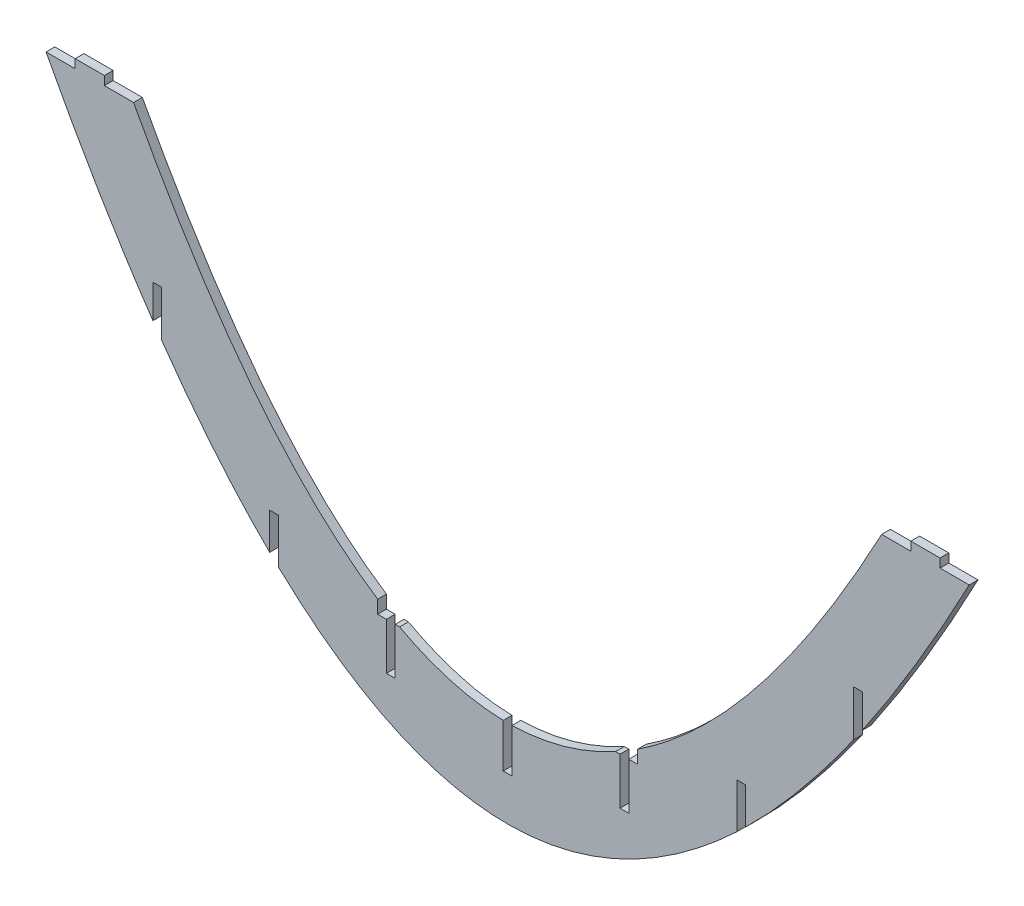
SolidWorks part; units mm, degrees
ref_plane "前视基准面" through (0, 0, 0) normal (0, 0, 1) x (1, 0, 0)
ref_plane "上视基准面" through (0, 0, 0) normal (0, 1, 0) x (1, 0, 0)
ref_plane "右视基准面" through (0, 0, 0) normal (1, 0, 0) x (0, 0, -1)
sketch "草图1" plane through (0, 0, 0) normal (0, 0, 1) x (1, 0, 0)
  line L0 (-158.115, 150.0021) -> (-128.1161, 150.0021)
  line L1 (128.1161, 150.0021) -> (158.115, 150.0021)
  spline S0 degree 2 poles (-178.3817, 190.9203) (0, -190.9203) (178.3817, 190.9203) knots 0 0 0 1 1 1 construction
  spline S1 degree 2 poles (-158.115, 150.0021) (0, -150.0021) (158.115, 150.0021) knots 0.056807 0.056807 0.056807 0.943193 0.943193 0.943193
  spline S2 degree 2 poles (-177.2656, 259.7365) (0, -199.7365) (177.2656, 259.7365) knots 0 0 0 1 1 1 construction
  spline S3 degree 2 poles (-128.1161, 150.0021) (0, -90.0021) (128.1161, 150.0021) knots 0.138632 0.138632 0.138632 0.861368 0.861368 0.861368
extrude "凸台-拉伸1" add sketch "草图1" along normal blind 3
sketch "草图2" plane through (0, 150.0021, 0) normal (0, 1, 0) x (1, 0, 0)
  line L0 (-158.115, -3) -> (-128.1161, 0)
  line L1 (128.1161, 0) -> (158.115, -3)
  line L2 (158.115, 0) -> (128.1161, 0) construction
  line L3 (138.1156, -3) -> (148.1156, -3)
  line L4 (138.1156, -3) -> (138.1156, 0)
  line L5 (138.1156, 0) -> (148.1156, 0)
  line L6 (148.1156, -3) -> (148.1156, 0)
  line L7 (138.1156, -3) -> (148.1156, 0) construction
  line L8 (138.1156, 0) -> (148.1156, -3) construction
  line L9 (-128.1161, 0) -> (-158.115, 0) construction
  line L10 (-148.1156, -3) -> (-138.1156, -3)
  line L11 (-148.1156, -3) -> (-148.1156, 0)
  line L12 (-148.1156, 0) -> (-138.1156, 0)
  line L13 (-138.1156, -3) -> (-138.1156, 0)
  line L14 (-148.1156, -3) -> (-138.1156, 0) construction
  line L15 (-148.1156, 0) -> (-138.1156, -3) construction
  point P8 (143.1156, -1.5)
  point P15 (-143.1156, -1.5)
  line M2 (-128.1161, 0) -> (-158.115, 0)
  line M4 (-158.115, -3) -> (-128.1161, -3)
extrude "凸台-拉伸2" add sketch "草图2" along normal blind 3 contours L1 L6 L5 L4 | L3 L6 L1 L4 | L0 L13 L11 M2 | L13 L0 L11 M4
sketch "草图3" plane through (0, 0, 0) normal (0, 0, -1) x (-1, 0, 0)
  line L14 (1.5, 0.0234) -> (1.5, 150.0021) construction
  line L15 (1.5, 15.0087) -> (1.5, 30.0164)
  line L16 (-1.5, 150.0021) -> (-1.5, 0.0234) construction
  line L17 (-1.5, 30.0164) -> (-1.5, 15.0087)
  line L18 (-44.5, 80.0009) -> (-44.5, 40.0009) construction
  line L19 (1.5, 15.0087) -> (-1.5, 15.0087)
  line L20 (-118.5, 99.992) -> (-121.5, 99.992)
  line L21 (-81.5, 52.3685) -> (-78.5, 52.3685)
  line L22 (1.5, 15.0087) -> (1.5, 30.0164)
  line L23 (1.5, 30.0164) -> (-1.5, 30.0164)
  line L24 (-1.5, 15.0087) -> (-1.5, 30.0164)
  line L25 (-44.5, 80.0009) -> (-44.5, 40.0009)
  line L26 (44.5, 40.0009) -> (44.5, 80.0009) construction
  line L27 (44.5, 40.0009) -> (44.5, 80.0009)
  line L28 (-38.5, 23.9686) -> (-41.5, 23.9686)
  line L29 (-121.5, 116.4004) -> (-118.5, 116.4004)
  line L30 (-121.5, 116.4004) -> (-121.5, 83.5836)
  line L31 (-121.5, 83.5836) -> (-118.5, 83.5836)
  line L32 (-118.5, 116.4004) -> (-118.5, 83.5836)
  line L33 (-81.5, 68.4006) -> (-78.5, 68.4006)
  line L34 (-81.5, 68.4006) -> (-81.5, 36.3363)
  line L35 (-81.5, 36.3363) -> (-78.5, 36.3363)
  line L36 (-78.5, 68.4006) -> (-78.5, 36.3363)
  line L37 (-41.5, 41.8588) -> (-38.5, 41.8588)
  line L38 (-41.5, 41.8588) -> (-41.5, 23.9686)
  line L39 (-44.5, 80.0009) -> (44.5, 80.0009)
  line L40 (-38.5, 41.8588) -> (-38.5, 23.9686)
  line L41 (38.5, 47.1948) -> (41.5, 47.1948)
  line L42 (38.5, 47.1948) -> (38.5, 23.9686)
  line L43 (44.5, 40.0009) -> (-44.5, 40.0009)
  line L44 (41.5, 47.1948) -> (41.5, 23.9686)
  line L45 (78.5, 68.4006) -> (81.5, 68.4006)
  line L46 (78.5, 68.4006) -> (78.5, 36.3363)
  line L47 (78.5, 36.3363) -> (81.5, 36.3363)
  line L48 (81.5, 68.4006) -> (81.5, 36.3363)
  line L49 (118.5, 116.4004) -> (121.5, 116.4004)
  line L50 (118.5, 116.4004) -> (118.5, 83.5836)
  line L51 (118.5, 83.5836) -> (121.5, 83.5836)
  line L52 (121.5, 116.4004) -> (121.5, 83.5836)
  line L53 (41.5, 23.9686) -> (38.5, 23.9686)
  line L54 (81.5, 52.3685) -> (78.5, 52.3685)
  line L55 (121.5, 99.992) -> (118.5, 99.992)
  parabola Q0 (-128.1161, 150.0021) -> (128.1161, 150.0021) focus (0, 64.1947) apex (0, 30) construction
  parabola Q1 (-1.5, 30.0164) -> (1.5, 30.0164) focus (0, 64.1947) apex (0, 30)
  spline M3 degree 2 poles (128.1161, 150.0021) (0, -90.0021) (-128.1161, 150.0021) knots 0.138632 0.138632 0.138632 0.861368 0.861368 0.861368
  spline M9 degree 2 poles (-158.115, 150.0021) (0, -150.0021) (158.115, 150.0021) knots 0.056807 0.056807 0.056807 0.943193 0.943193 0.943193
extrude "切除-拉伸1" cut sketch "草图3" against normal through all contours L44 L41 L42 M3 | L44 L43 L27 M3 | L44 L42 L43 M3 | L53 L44 L43 L42 | L43 L42 M3 | L41 L44 L27 L39 L25 L37 L40 L43 L42 M3 | L43 L40 M3 | L40 L37 M3 | L43 L40 L37 L38 M3 | L43 L38 L37 L25 M3 | L40 L43 L38 L28 | L19 L15 L17 M3 | L32 L20 L30 M9 | L36 L21 L34 M9 | L48 L54 L46 M9 | L52 L55 L50 M9
